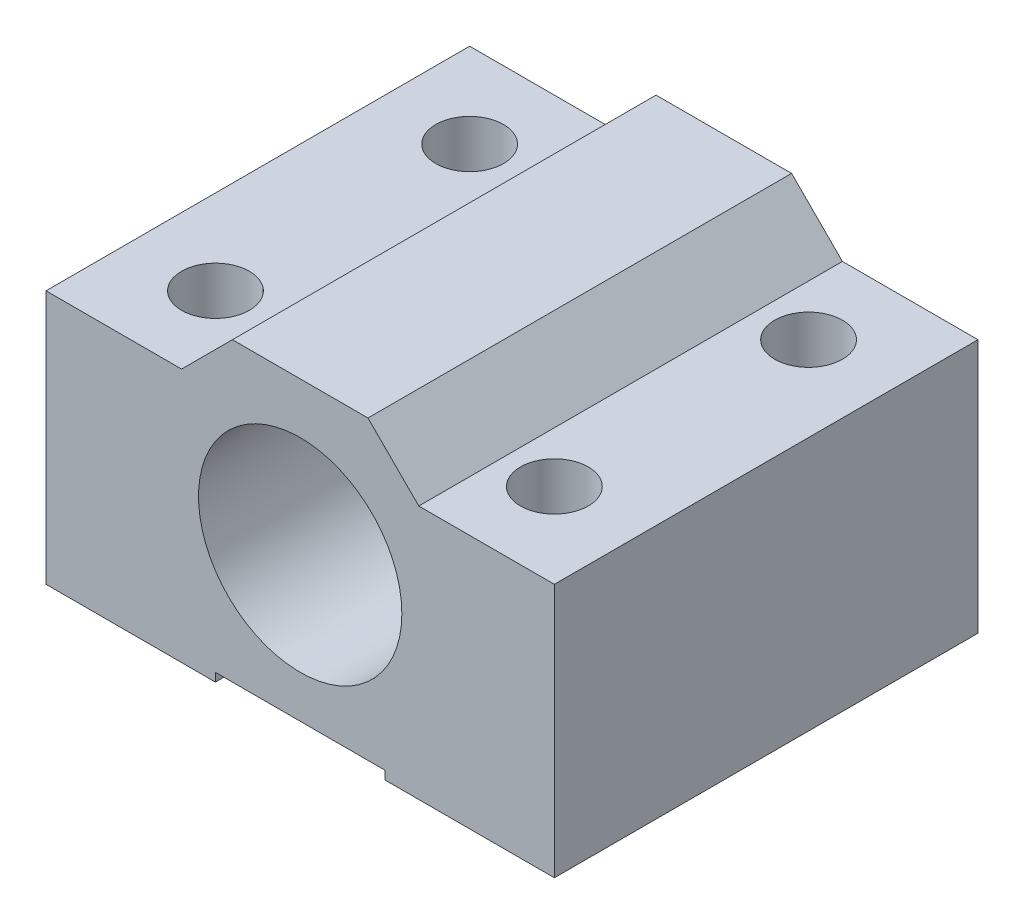
SolidWorks part; units mm, degrees
ref_plane "Plan de face" through (0, 0, 0) normal (0, 0, 1) x (1, 0, 0)
ref_plane "Plan de dessus" through (0, 0, 0) normal (0, 1, 0) x (1, 0, 0)
ref_plane "Plan de droite" through (0, 0, 0) normal (1, 0, 0) x (0, 0, -1)
sketch "Esquisse1" plane through (0, 0, 0) normal (0, 0, 1) x (1, 0, 0)
  line L0 (0, 0) -> (0, 18) construction
  line L1 (15, 0) -> (-15, 0)
  line L2 (-15, 0) -> (-15, 15)
  line L3 (-15, 15) -> (-7, 15)
  line L4 (-7, 15) -> (-4, 18)
  line L5 (-4, 18) -> (4, 18)
  line L6 (7, 15) -> (4, 18)
  line L7 (15, 15) -> (7, 15)
  line L8 (15, 0) -> (15, 15)
  dimension "D1" = 15
  dimension "D2" = 15
  dimension "D3" = 3
  dimension "D4" = 135
  dimension "D5" = 8
extrude "Boss.-Extru.1" add sketch "Esquisse1" along normal blind 25
sketch "Esquisse2" plane through (0, 0, 25) normal (0, 0, 1) x (1, 0, 0)
  line L0 (0, 0) -> (0, 9) construction
  circle A0 centre (0, 9) radius 6
  dimension "D1" = 12
  dimension "D2" = 9
extrude "Enlèv. mat.-Extru.1" cut sketch "Esquisse2" against normal up to vertex (25 mm away) up to point (15, 15, 0)
sketch "Esquisse3" plane through (0, 15, 0) normal (0, 1, 0) x (1, 0, 0)
  line L0 (0, 0) -> (0, -25) construction
  line L1 (4, -25) -> (-4, -25) construction
  line L2 (-15, -12.5) -> (15, -12.5) construction
  line L3 (-15, -25) -> (-15, 0) construction
  line L4 (15, -25) -> (15, 0) construction
  circle A0 centre (-10, -5) radius 2
  circle A1 centre (10, -5) radius 2
  circle A2 centre (10, -20) radius 2
  circle A3 centre (-10, -20) radius 2
  dimension "D1" = 4
  dimension "D2" = 20
  dimension "D3" = 15
extrude "Enlèv. mat.-Extru.2" cut sketch "Esquisse3" against normal through all
sketch "Esquisse4" plane through (0, 0, 0) normal (0, -1, 0) x (1, 0, 0)
  line L0 (-15, 25) -> (15, 25) construction
  line L1 (-5, 25) -> (5, 25)
  line L2 (-5, 25) -> (-5, 0)
  line L3 (-5, 0) -> (5, 0)
  line L4 (5, 25) -> (5, 0)
  line L5 (-15, 0) -> (15, 0) construction
  line L6 (0, 0) -> (0, 25) construction
  dimension "D1" = 10
extrude "Enlèv. mat.-Extru.3" cut sketch "Esquisse4" against normal blind 0.5
